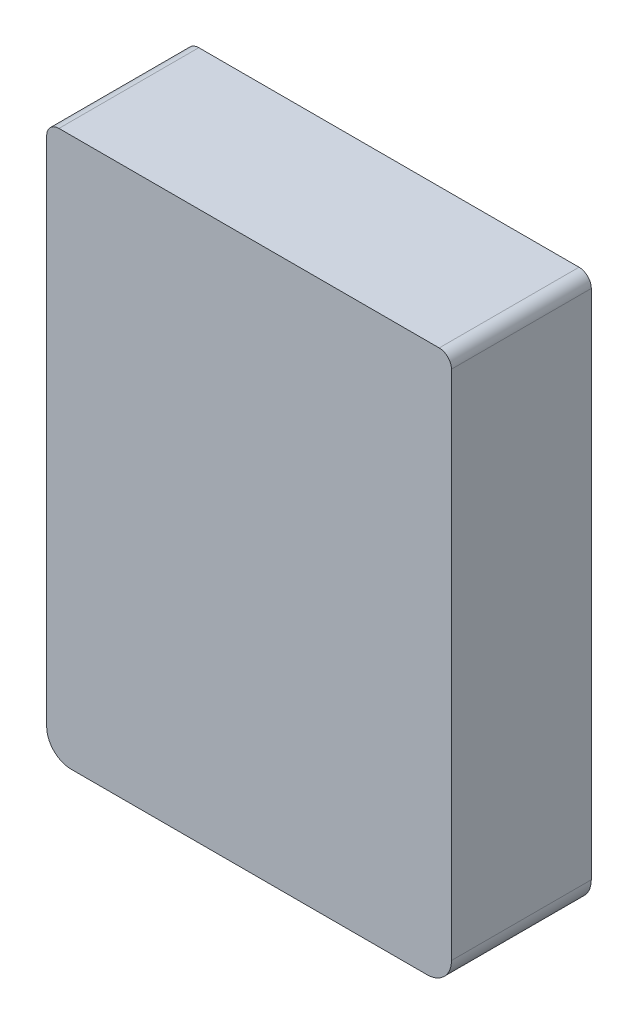
SolidWorks part; units mm, degrees
ref_plane "Front Plane" through (0, 0, 0) normal (0, 0, 1) x (1, 0, 0)
ref_plane "Top Plane" through (0, 0, 0) normal (0, 1, 0) x (1, 0, 0)
ref_plane "Right Plane" through (0, 0, 0) normal (1, 0, 0) x (0, 0, -1)
sketch "Sketch1" plane through (0, 0, 0) normal (0, 0, 1) x (1, 0, 0)
  line L2 (28, 250) -> (28, 307.5)
  line L4 (94, 224) -> (94, 250)
  line L5 (32, 220) -> (90, 220)
  line L6 (28, 250) -> (28, 224)
  line L7 (94, 250) -> (28, 250)
  line L8 (94, 224) -> (94, 250)
  line L9 (32, 220) -> (90, 220)
  line L10 (28, 250) -> (28, 224)
  line L12 (30.5, 309.5) -> (91.5, 309.5) construction
  line L13 (30.5, 309.5) -> (91.5, 309.5)
  line L14 (94, 250) -> (94, 307.5)
  line L17 (91.5, 309.5) -> (92, 309.5)
  line L18 (30, 309.5) -> (30.5, 309.5)
  arc A0 (30, 309.5) -> (28, 307.5) centre (30, 307.5) ccw
  arc A1 (94, 307.5) -> (92, 309.5) centre (92, 307.5) ccw
  arc A2 (90, 220) -> (94, 224) centre (90, 224) ccw
  arc A3 (28, 224) -> (32, 220) centre (32, 224) ccw
  arc A4 (90, 220) -> (94, 224) centre (90, 224) ccw
  arc A5 (28, 224) -> (32, 220) centre (32, 224) ccw
  dimension "D2" = 2
  dimension "D1" = 0
extrude "Boss-Extrude1" add sketch "Sketch1" along normal up to surface (22.8 mm away)
